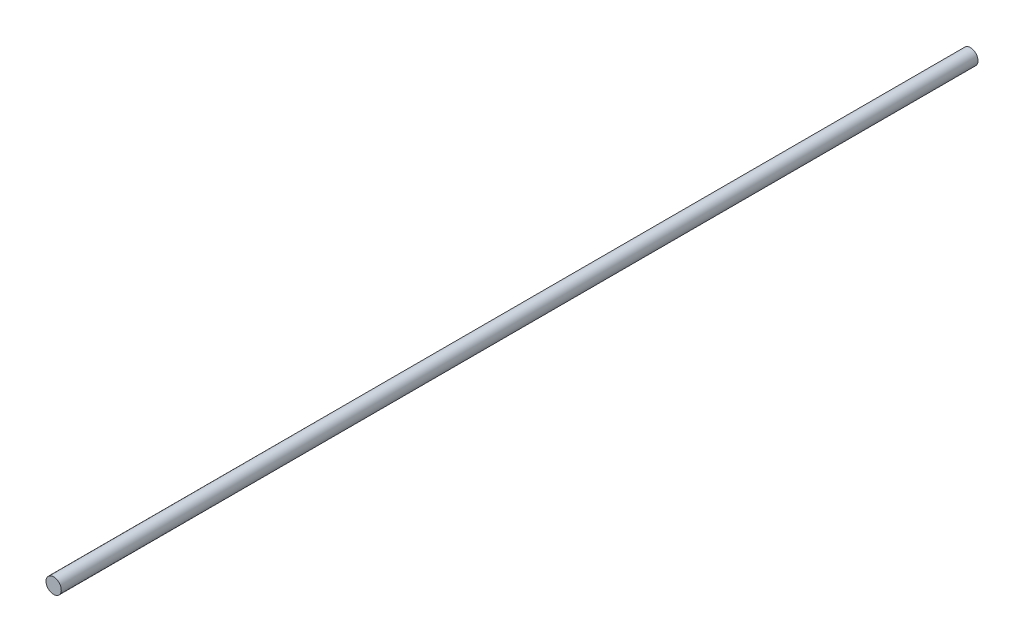
SolidWorks part; units mm, degrees
material "Aluminum"
ref_plane "Front Plane" through (0, 0, 0) normal (0, 0, 1) x (1, 0, 0)
ref_plane "Top Plane" through (0, 0, 0) normal (0, 1, 0) x (1, 0, 0)
ref_plane "Right Plane" through (0, 0, 0) normal (1, 0, 0) x (0, 0, -1)
sketch "Sketch1" plane through (0, 0, 0) normal (0, 0, 1) x (1, 0, 0)
  circle A0 centre (0, 2.7823) radius 6.35
  dimension "D1" = 12.7
extrude "Boss-Extrude1" add sketch "Sketch1" along normal blind 762
equation "\"Diameter\"= 0.5in"
equation "\"length\"= \"MaxDeflection\" * \"Area\" * \"E\" / \"Force\""
equation "\"Force\"= 500"
equation "\"E\"= 8.5e6"
equation "\"MaxDeflection\"= 0.009"
equation "\"Area\"= \"Diameter\" ^ 2 * pi / 4"
